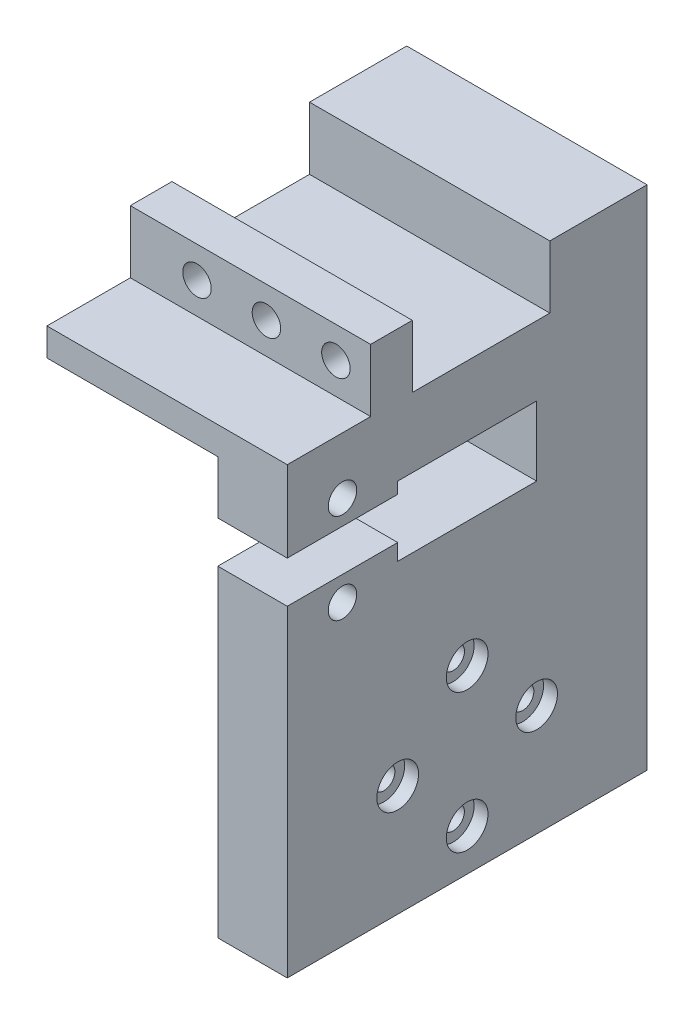
SolidWorks part; units mm, degrees
ref_plane "前视基准面" through (0, 0, 0) normal (0, 0, 1) x (1, 0, 0)
ref_plane "上视基准面" through (0, 0, 0) normal (0, 1, 0) x (1, 0, 0)
ref_plane "右视基准面" through (0, 0, 0) normal (1, 0, 0) x (0, 0, -1)
sketch "草图1" plane through (0, 0, 0) normal (0, 1, 0) x (1, 0, 0)
  line L1 (-15, -19.9) -> (15, -19.9)
  line L2 (-15, -19.9) -> (-15, 19.9)
  line L3 (-15, 19.9) -> (15, 19.9)
  line L4 (15, -19.9) -> (15, 19.9)
  line L5 (-15, -19.9) -> (15, 19.9) construction
  line L6 (-15, 19.9) -> (15, -19.9) construction
  point P0 (0, 0)
  dimension "D1" = 39.8
  dimension "D2" = 30
extrude "凸台-拉伸1" add sketch "草图1" along normal blind 4 contours L1 L4 L3 L2
ref_plane "基准面1" through (0, 4, 0) normal (0, 1, 0) x (1, 0, 0)
sketch "草图2" plane through (0, 4, 0) normal (0, 1, 0) x (1, 0, 0)
  line L0 (-15, -19.9) -> (-15, 19.9) construction
  line L1 (15, 19.9) -> (-15, 19.9)
  line L2 (15, 19.9) -> (15, 5.9)
  line L3 (15, 5.9) -> (-15, 5.9)
  line L4 (-15, 19.9) -> (-15, 5.9)
  dimension "D1" = 14
extrude "凸台-拉伸2" add sketch "草图2" along normal blind 9
sketch "草图3" plane through (0, 4, 0) normal (0, 1, 0) x (1, 0, 0)
  line L0 (-15, -19.9) -> (-15, 5.9) construction
  line L1 (15, -19.9) -> (-15, -19.9)
  line L2 (15, -19.9) -> (15, -13.9)
  line L3 (15, -13.9) -> (-15, -13.9)
  line L4 (-15, -19.9) -> (-15, -13.9)
  dimension "D1" = 6
extrude "凸台-拉伸3" add sketch "草图3" along normal blind 9
ref_plane "基准面2" through (0, 0, 0) normal (0, -1, 0) x (-1, 0, 0)
sketch "草图4" plane through (0, 0, 0) normal (0, -1, 0) x (-1, 0, 0)
  line L0 (15, -19.9) -> (-15, -19.9) construction
  line L1 (-5, -19.9) -> (-15, -19.9)
  line L2 (-5, -19.9) -> (-5, 19.9)
  line L3 (-5, 19.9) -> (-15, 19.9)
  line L4 (-15, -19.9) -> (-15, 19.9)
  line L5 (15, 19.9) -> (-15, 19.9) construction
  dimension "D2" = 10
extrude "凸台-拉伸4" add sketch "草图4" along normal blind 60
ref_plane "基准面3" through (15, 0, 0) normal (1, 0, 0) x (0, 0, -1)
sketch "草图5" plane through (15, 0, 0) normal (1, 0, 0) x (0, 0, -1)
  line L0 (19.9, 0) -> (-19.9, 0) construction
  line L1 (4, -16) -> (-16, -16)
  line L2 (4, -16) -> (4, -6)
  line L3 (4, -6) -> (-16, -6)
  line L4 (-16, -16) -> (-16, -6)
  line L9 (19.9, -60) -> (19.9, 13) construction
  dimension "D1" = 10
  dimension "D2" = 6
  dimension "D3" = 20
  dimension "D4" = 15.9
extrude "切除-拉伸1" cut sketch "草图5" against normal through all
sketch "草图6" plane through (15, 0, 0) normal (1, 0, 0) x (0, 0, -1)
  line L0 (-16, -6) -> (-16, -16) construction
  line L1 (-16, -13.6511) -> (-19.9, -13.6511)
  line L2 (-16, -13.6511) -> (-16, -7.6511)
  line L3 (-16, -7.6511) -> (-19.9, -7.6511)
  line L4 (-19.9, -13.6511) -> (-19.9, -7.6511)
  line L5 (-19.9, -60) -> (-19.9, 13) construction
  dimension "D1" = 6
extrude "切除-拉伸2" cut sketch "草图6" against normal through all
ref_plane "基准面4" through (-15, 0, 0) normal (-1, 0, 0) x (0, 0, 1)
sketch "草图8" plane through (-15, 0, 0) normal (-1, 0, 0) x (0, 0, 1)
  line L1 (10.89, 4) -> (-10.89, 4) construction
  line L2 (19.9, 13) -> (19.9, 0) construction
  line L4 (19.9, 4) -> (31.9, 4)
  line L5 (19.9, 4) -> (19.9, 0)
  line L6 (19.9, 0) -> (31.9, 0)
  line L7 (31.9, 4) -> (31.9, 0)
  dimension "D1" = 12
extrude "凸台-拉伸5" add sketch "草图8" against normal blind 30
ref_plane "基准面5" through (5, 0, 0) normal (-1, 0, 0) x (0, 0, 1)
sketch "草图9" plane through (5, 0, 0) normal (-1, 0, 0) x (0, 0, 1)
  line L1 (19.9, 0) -> (31.9, 0)
  line L2 (19.9, 0) -> (19.9, -7.6511)
  line L3 (19.9, -7.6511) -> (31.9, -7.6511)
  line L4 (31.9, 0) -> (31.9, -7.6511)
  line L5 (19.9, -13.6511) -> (31.9, -13.6511)
  line L6 (19.9, -13.6511) -> (19.9, -60)
  line L7 (19.9, -60) -> (31.9, -60)
  line L8 (31.9, -13.6511) -> (31.9, -60)
extrude "凸台-拉伸6" add sketch "草图9" against normal blind 10
ref_plane "基准面6" through (5, 0, 0) normal (-1, 0, 0) x (0, 0, 1)
sketch "草图11" plane through (5, 0, 0) normal (-1, 0, 0) x (0, 0, 1)
  line L1 (31.9, -60) -> (21.9, -60)
  line L2 (31.9, -60) -> (31.9, -40)
  line L3 (31.9, -40) -> (21.9, -40)
  line L4 (21.9, -60) -> (21.9, -40)
  line L5 (-19.9, -60) -> (-9.9, -60)
  line L6 (-19.9, -60) -> (-19.9, -40)
  line L7 (-19.9, -40) -> (-9.9, -40)
  line L8 (-9.9, -60) -> (-9.9, -40)
extrude "凸台-拉伸8" [suppressed] add sketch "草图11" along normal blind 24.6
ref_plane "基准面7" through (5, 0, 0) normal (-1, 0, 0) x (0, 0, 1)
sketch "草图12" plane through (5, 0, 0) normal (-1, 0, 0) x (0, 0, 1)
  line L0 (6, -60) -> (6, -54)
  line L1 (31.9, -60) -> (-19.9, -60) construction
  line L2 (6, -54) -> (6, -34)
sketch "草图13" plane through (5, 0, 0) normal (-1, 0, 0) x (0, 0, 1)
  circle A0 centre (-4, -44) radius 1.6
  circle A1 centre (6, -34) radius 1.615
  circle A2 centre (16, -44) radius 1.6
  circle A3 centre (6, -54) radius 1.6
extrude "切除-拉伸3" cut sketch "草图13" against normal through all
ref_plane "基准面8" through (15, 0, 0) normal (1, 0, 0) x (0, 0, -1)
sketch "草图14" plane through (15, 0, 0) normal (1, 0, 0) x (0, 0, -1)
  circle A0 centre (-6, -34) radius 3
  circle A1 centre (-16, -44) radius 3
  circle A2 centre (-6, -54) radius 3
  circle A3 centre (4, -44) radius 3
extrude "切除-拉伸4" cut sketch "草图14" against normal blind 2
ref_plane "基准面9" through (0, 0, 19.9) normal (0, 0, 1) x (1, 0, 0)
sketch "草图16" plane through (0, 0, 19.9) normal (0, 0, 1) x (1, 0, 0)
  line L0 (-15, 8.5) -> (-13.5, 8.5)
  line L1 (-15, 13) -> (-15, 4) construction
  line L2 (-13.5, 8.5) -> (-6.5, 8.5)
  line L3 (-6.5, 8.5) -> (-3.5, 8.5)
  line L4 (-3.5, 8.5) -> (3.5, 8.5)
  line L5 (3.5, 8.5) -> (6.5, 8.5)
  line L6 (6.5, 8.5) -> (13.5, 8.5)
  circle A0 centre (-10, 8.5) radius 2.05
  circle A1 centre (0, 8.5) radius 2.05
  circle A2 centre (10, 8.5) radius 2.05
extrude "切除-拉伸5" cut sketch "草图16" against normal up to next contours A1 | A2 | A0
ref_plane "基准面10" through (5, 0, 0) normal (-1, 0, 0) x (0, 0, 1)
sketch "草图18" plane through (5, 0, 0) normal (-1, 0, 0) x (0, 0, 1)
  line L0 (31.9, -7.6511) -> (31.9, -0.6511)
  line L1 (31.9, -7.6511) -> (31.9, 0) construction
  line L2 (31.9, -0.6511) -> (16, -0.6511)
  line L3 (16, -0.6511) -> (16, -7.6511)
  line L4 (16, -7.6511) -> (31.9, -7.6511)
  line L5 (31.9, -4.1511) -> (16, -4.1511)
  line L6 (23.95, -0.6511) -> (23.95, -7.6511)
  line L9 (31.9, -13.6511) -> (31.9, -20.6511)
  line L10 (31.9, -60) -> (31.9, -13.6511) construction
  line L11 (31.9, -20.6511) -> (16, -20.6511)
  line L12 (16, -20.6511) -> (16, -13.6511)
  line L13 (16, -13.6511) -> (31.9, -13.6511)
  line L14 (23.95, -13.6511) -> (23.95, -20.6511)
  circle A2 centre (23.95, -4.1511) radius 2.05
  circle A3 centre (23.95, -17.1511) radius 2.05
extrude "切除-拉伸7" cut sketch "草图18" against normal through all contours A2 | A3
fillet "圆角1" [suppressed] radius 1
fillet "圆角2" [suppressed] radius 1
fillet "圆角3" [suppressed] radius 1
fillet "圆角4" [suppressed] radius 1
fillet "圆角5" [suppressed] radius 1
fillet "圆角6" [suppressed] radius 1
fillet "圆角9" [suppressed] radius 1
fillet "圆角11" [suppressed] radius 1
fillet "圆角12" [suppressed] radius 1
fillet "圆角13" [suppressed] radius 1
fillet "圆角14" [suppressed] radius 1
fillet "圆角15" [suppressed] radius 1
ref_plane "基准面11" through (-15, 0, 0) normal (-1, 0, 0) x (0, 0, 1)
sketch "草图21" plane through (-15, 0, 0) normal (-1, 0, 0) x (0, 0, 1)
  line L0 (31.9, 0) -> (31.9, 4)
  line L1 (31.9, 4) -> (19.9, 4)
  line L2 (19.9, 4) -> (19.9, 13)
  line L3 (19.9, 13) -> (13.9, 13)
  line L4 (13.9, 13) -> (13.9, 4)
  line L5 (13.9, 4) -> (-5.9, 4)
  line L6 (-5.9, 4) -> (-5.9, 13)
  line L7 (-5.9, 13) -> (-19.9, 13)
  line L8 (-19.9, 13) -> (-19.9, 0)
  line L9 (-19.9, 0) -> (31.9, 0)
extrude "Stopper" add sketch "草图21" along normal blind 4.6
